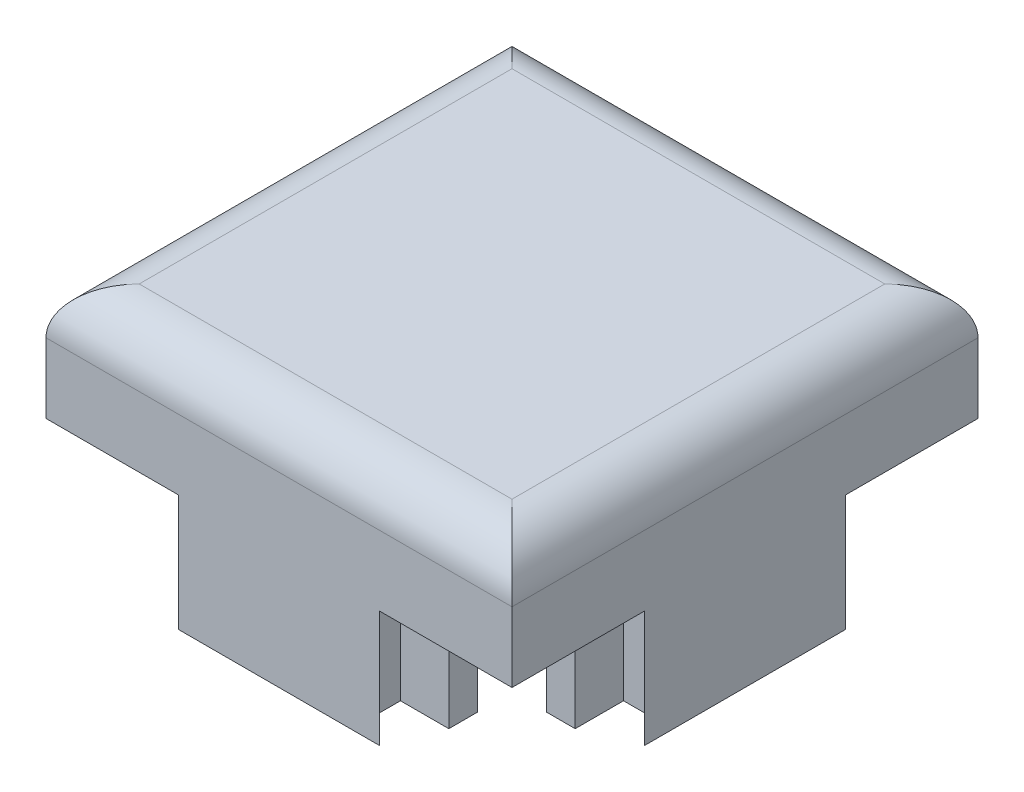
SolidWorks part; units mm, degrees
ref_plane "Alzado" through (0, 0, 0) normal (0, 0, 1) x (1, 0, 0)
ref_plane "Planta" through (0, 0, 0) normal (0, 1, 0) x (1, 0, 0)
ref_plane "Vista lateral" through (0, 0, 0) normal (1, 0, 0) x (0, 0, -1)
sketch "Croquis1" plane through (0, 0, 0) normal (0, 1, 0) x (1, 0, 0)
  line L1 (-10, -10) -> (10, -10) construction
  line L2 (-10, -10) -> (-10, 10) construction
  line L3 (-10, 10) -> (10, 10) construction
  line L4 (10, -10) -> (10, 10) construction
  line L5 (-10, -10) -> (10, 10) construction
  line L6 (-10, 10) -> (10, -10) construction
  point P0 (0, 0)
  dimension "D1" = 20
  dimension "D2" = 20
sketch "Croquis2" plane through (0, 0, 0) normal (0, 1, 0) x (1, 0, 0)
  line L0 (0, 15.0494) -> (0, -15.2637) construction
  line L1 (17.7146, 0) -> (-12.7501, 0) construction
  line L2 (-3.881, 9.7) -> (-4.3152, 10)
  line L4 (-10, 10) -> (10, 10) construction
  line L5 (-4.3152, 10) -> (4.3152, 10)
  line L6 (5.1746, 6.6571) -> (2.6892, 4.1717)
  line L7 (5.1746, 7.8869) -> (5.1746, 6.6571)
  line L8 (3.1001, 7.8869) -> (5.1746, 7.8869)
  line L9 (3.1001, 9.0077) -> (3.1001, 7.8869)
  line L10 (3.881, 9.7) -> (3.1001, 9.0077)
  line L11 (-3.881, 9.7) -> (-3.1001, 9.0077)
  line L12 (-3.1001, 9.0077) -> (-3.1001, 7.8869)
  line L13 (-3.1001, 7.8869) -> (-5.1746, 7.8869)
  line L14 (-5.1746, 7.8869) -> (-5.1746, 6.6571)
  line L15 (-5.1746, 6.6571) -> (-2.6892, 4.1717)
  line L16 (-2.6892, 4.1717) -> (2.6892, 4.1717)
  line L17 (3.881, 9.7) -> (4.3152, 10)
  line L18 (10, 4.3152) -> (10, -4.3152)
  line L19 (9.7, -3.881) -> (10, -4.3152)
  line L20 (9.7, -3.881) -> (9.0077, -3.1001)
  line L21 (9.0077, -3.1001) -> (7.8869, -3.1001)
  line L22 (7.8869, -3.1001) -> (7.8869, -5.1746)
  line L23 (7.8869, -5.1746) -> (6.6571, -5.1746)
  line L24 (6.6571, -5.1746) -> (4.1717, -2.6892)
  line L25 (4.1717, 2.6892) -> (4.1717, -2.6892)
  line L26 (6.6571, 5.1746) -> (4.1717, 2.6892)
  line L27 (7.8869, 5.1746) -> (6.6571, 5.1746)
  line L28 (7.8869, 3.1001) -> (7.8869, 5.1746)
  line L29 (9.0077, 3.1001) -> (7.8869, 3.1001)
  line L30 (9.7, 3.881) -> (9.0077, 3.1001)
  line L31 (9.7, 3.881) -> (10, 4.3152)
  line L32 (4.3152, -10) -> (-4.3152, -10)
  line L33 (-3.881, -9.7) -> (-4.3152, -10)
  line L34 (-3.881, -9.7) -> (-3.1001, -9.0077)
  line L35 (-3.1001, -9.0077) -> (-3.1001, -7.8869)
  line L36 (-3.1001, -7.8869) -> (-5.1746, -7.8869)
  line L37 (-5.1746, -7.8869) -> (-5.1746, -6.6571)
  line L38 (-5.1746, -6.6571) -> (-2.6892, -4.1717)
  line L39 (2.6892, -4.1717) -> (-2.6892, -4.1717)
  line L40 (5.1746, -6.6571) -> (2.6892, -4.1717)
  line L41 (5.1746, -7.8869) -> (5.1746, -6.6571)
  line L42 (3.1001, -7.8869) -> (5.1746, -7.8869)
  line L43 (3.1001, -9.0077) -> (3.1001, -7.8869)
  line L44 (3.881, -9.7) -> (3.1001, -9.0077)
  line L45 (3.881, -9.7) -> (4.3152, -10)
  line L46 (-10, -4.3152) -> (-10, 4.3152)
  line L47 (-9.7, 3.881) -> (-10, 4.3152)
  line L48 (-9.7, 3.881) -> (-9.0077, 3.1001)
  line L49 (-9.0077, 3.1001) -> (-7.8869, 3.1001)
  line L50 (-7.8869, 3.1001) -> (-7.8869, 5.1746)
  line L51 (-7.8869, 5.1746) -> (-6.6571, 5.1746)
  line L52 (-6.6571, 5.1746) -> (-4.1717, 2.6892)
  line L53 (-4.1717, -2.6892) -> (-4.1717, 2.6892)
  line L54 (-6.6571, -5.1746) -> (-4.1717, -2.6892)
  line L55 (-7.8869, -5.1746) -> (-6.6571, -5.1746)
  line L56 (-7.8869, -3.1001) -> (-7.8869, -5.1746)
  line L57 (-9.0077, -3.1001) -> (-7.8869, -3.1001)
  line L58 (-9.7, -3.881) -> (-9.0077, -3.1001)
  line L59 (-9.7, -3.881) -> (-10, -4.3152)
  point P10 (0, 4.1717)
  point P23 (0, 10)
  point P68 (0, 0)
  dimension "D1" = 4
extrude "Saliente-Extruir1" add sketch "Croquis2" along normal blind 5
sketch "Croquis3" plane through (0, 5, 0) normal (0, 1, 0) x (1, 0, 0)
  line L0 (0, 10) -> (0, -10) construction
  line L1 (4.3152, 10) -> (-4.3152, 10) construction
  line L2 (-4.3152, -10) -> (4.3152, -10) construction
  line L3 (-10, 0) -> (10, 0) construction
  line L4 (-10, 4.3152) -> (-10, -4.3152) construction
  line L5 (10, -4.3152) -> (10, 4.3152) construction
  line L6 (10, 0) -> (10, 10) construction
  line L7 (10, 10) -> (0, 10) construction
  line L9 (-10, -10) -> (10, -10)
  line L10 (-10, -10) -> (-10, 10)
  line L11 (-10, 10) -> (10, 10)
  line L12 (10, -10) -> (10, 10)
  line L13 (-10, -10) -> (10, 10) construction
  line L14 (-10, 10) -> (10, -10) construction
  point P13 (0, 0)
extrude "Saliente-Extruir2" add sketch "Croquis3" along normal blind 5
fillet "Redondeo1" radius 2 4 edges at (-10, 10, 0) (0, 10, 10) (10, 10, 0) (0, 10, -10)
